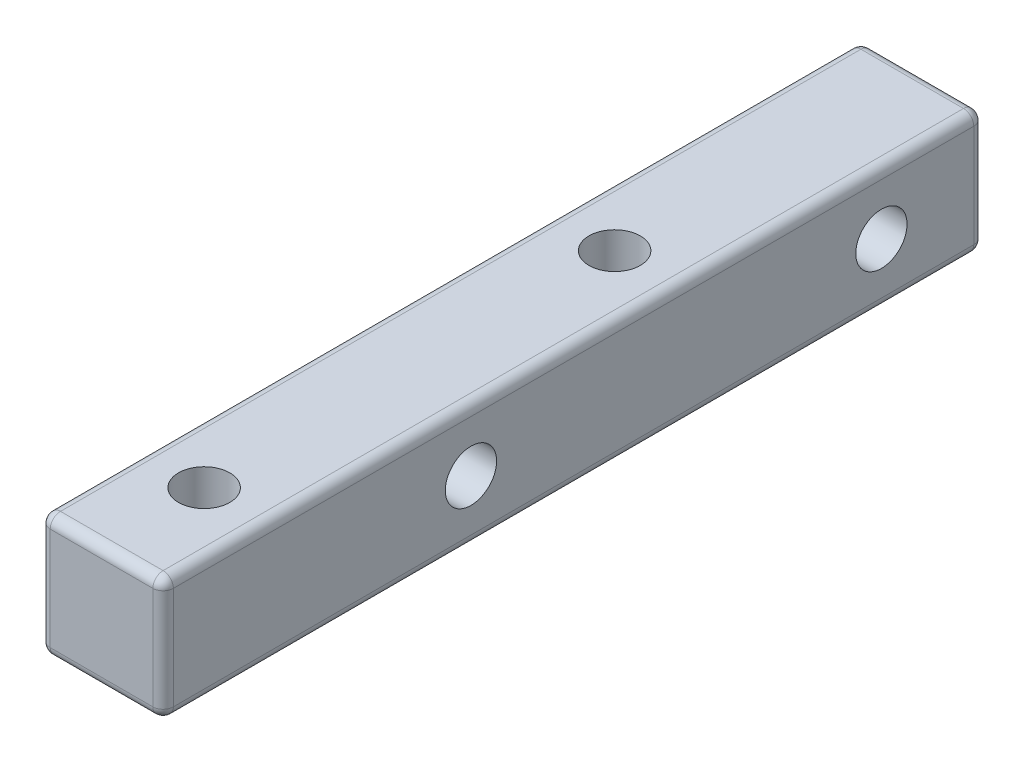
SolidWorks part; units mm, degrees
ref_plane "前视基准面" through (0, 0, 0) normal (0, 0, 1) x (1, 0, 0)
ref_plane "上视基准面" through (0, 0, 0) normal (0, 1, 0) x (1, 0, 0)
ref_plane "右视基准面" through (0, 0, 0) normal (1, 0, 0) x (0, 0, -1)
sketch "草图1" plane through (0, 0, 0) normal (0, 0, 1) x (1, 0, 0)
  line L1 (-3, -3) -> (3, -3)
  line L2 (-3, -3) -> (-3, 3)
  line L3 (-3, 3) -> (3, 3)
  line L4 (3, -3) -> (3, 3)
  line L5 (-3, -3) -> (3, 3) construction
  line L6 (-3, 3) -> (3, -3) construction
  point P0 (0, 0)
  dimension "D1" = 6
extrude "凸台-拉伸1" add sketch "草图1" along normal blind 40
sketch "草图2" plane through (-3, 0, 0) normal (-1, 0, 0) x (0, 0, 1)
  line L0 (5, 0) -> (25, 0) construction
  dimension "D1" = 5
  dimension "D2" = 20
sketch "草图3" plane through (0, 3, 0) normal (0, 1, 0) x (1, 0, 0)
  line L0 (0, -35) -> (0, -15) construction
  line L1 (3, -40) -> (-3, -40) construction
  point P5 (0, -40)
  dimension "D1" = 5
  dimension "D2" = 20
hole_wizard "M3 螺纹孔1" positions "草图4" profile "草图5" tap size "M3" standard "GB" end condition through all
sketch "草图4" plane through (0, 3, 0) normal (0, 1, 0) x (1, 0, 0)
  point P0 (0, -35)
  point P3 (0, -15)
sketch "草图5" plane through (0, 3, 35) normal (1, 0, 0) x (0, 0, 1)
  line L0 (0, 0) -> (0, 6)
  line L1 (0, 6) -> (1.25, 6)
  line L2 (1.25, 6) -> (1.25, 0)
  line L5 (1.25, 0) -> (0, 0)
  line L11 (0, -6.35) -> (0, 107.95) construction
  dimension "通孔螺纹孔钻头直径" = 2.5
  dimension "通孔螺纹孔钻头深度" = 6
cosmetic thread "孔螺蚊线1" parameters "D2"=3
cosmetic thread "孔螺蚊线2" parameters "D2"=3
hole_wizard "M3 螺纹孔2" positions "草图6" profile "草图7" tap size "M3" standard "GB" end condition through all
sketch "草图6" plane through (-3, 0, 0) normal (-1, 0, 0) x (0, 0, 1)
  point P0 (5, 0)
  point P3 (25, 0)
sketch "草图7" plane through (-3, 0, 5) normal (0, 1, 0) x (0, 0, 1)
  line L0 (0, 0) -> (0, 6)
  line L1 (0, 6) -> (1.25, 6)
  line L2 (1.25, 6) -> (1.25, 0)
  line L5 (1.25, 0) -> (0, 0)
  line L11 (0, -6.35) -> (0, 107.95) construction
  dimension "通孔螺纹孔钻头直径" = 2.5
  dimension "通孔螺纹孔钻头深度" = 6
cosmetic thread "孔螺蚊线3" parameters "D2"=3
cosmetic thread "孔螺蚊线4" parameters "D2"=3
fillet "圆角1" radius 0.5 12 edges at (0, -3, 40) (-3, 0, 40) (0, 3, 40) (3, 0, 40) (0, 3, 0) (-3, 0, 0) (0, -3, 0) (3, 0, 0) (3, -3, 20) (-3, -3, 20) (3, 3, 20) (-3, 3, 20)
sketch "草图8" plane through (0, 3, 0) normal (0, 1, 0) x (1, 0, 0)
  line L0 (0, -15) -> (0, -35) construction
sketch "草图9" plane through (3, 0, 0) normal (1, 0, 0) x (0, 0, -1)
  line L0 (-5, 0) -> (-25, 0) construction
sketch "草图10" plane through (0, -3, 0) normal (0, -1, 0) x (1, 0, 0)
  line L0 (0, 15) -> (0, 35) construction
sketch "草图11" plane through (-3, 0, 0) normal (-1, 0, 0) x (0, 0, 1)
  line L0 (5, 0) -> (25, 0) construction
